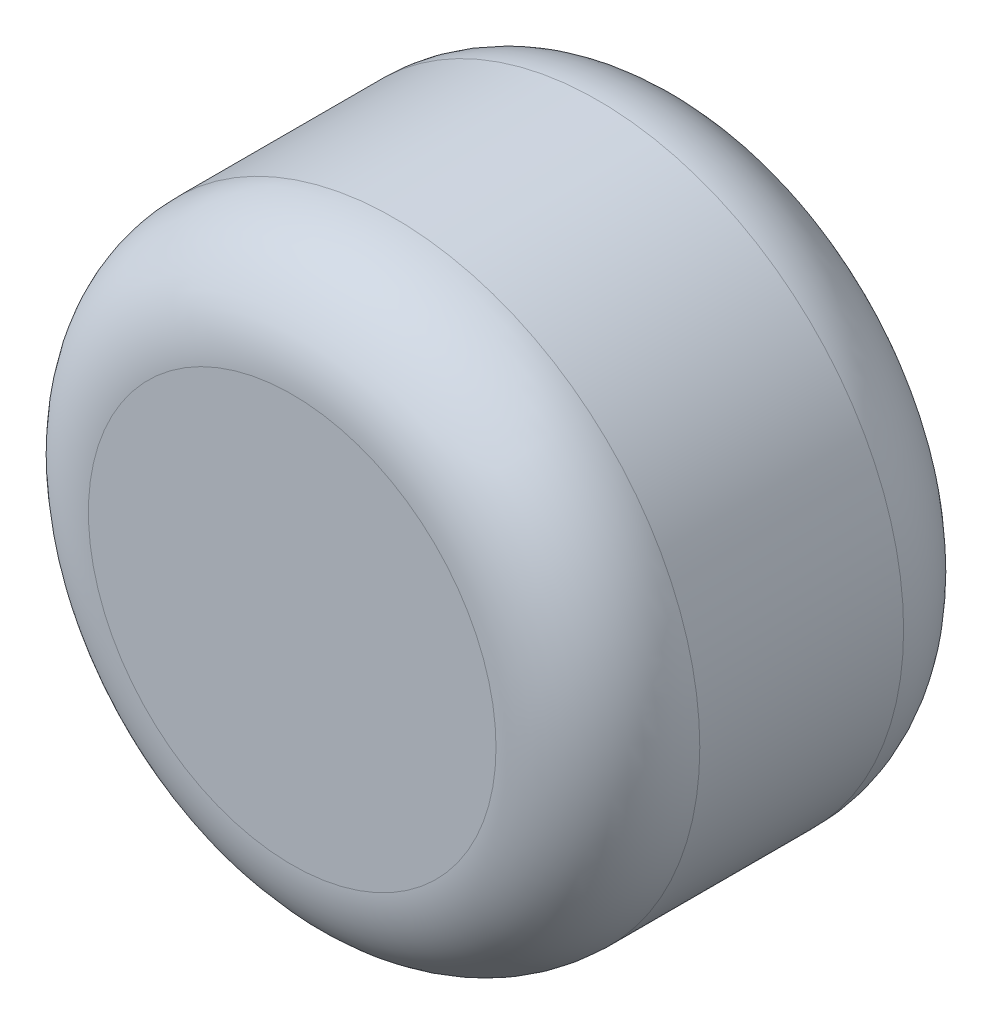
SolidWorks part; units mm, degrees
ref_plane "Plan de face" through (0, 0, 0) normal (0, 0, 1) x (1, 0, 0)
ref_plane "Plan de dessus" through (0, 0, 0) normal (0, 1, 0) x (1, 0, 0)
ref_plane "Plan de droite" through (0, 0, 0) normal (1, 0, 0) x (0, 0, -1)
sketch "Esquisse1" plane through (0, 0, 0) normal (0, 0, 1) x (1, 0, 0)
  circle A0 centre (0, 0) radius 76.2
  dimension "D1" = 152.4
extrude "Boss.-Extru.1" add sketch "Esquisse1" along normal blind 101.6
fillet "Congé1" radius 25.4 2 edges at (76.2, 0, 0) (76.2, 0, 101.6)
